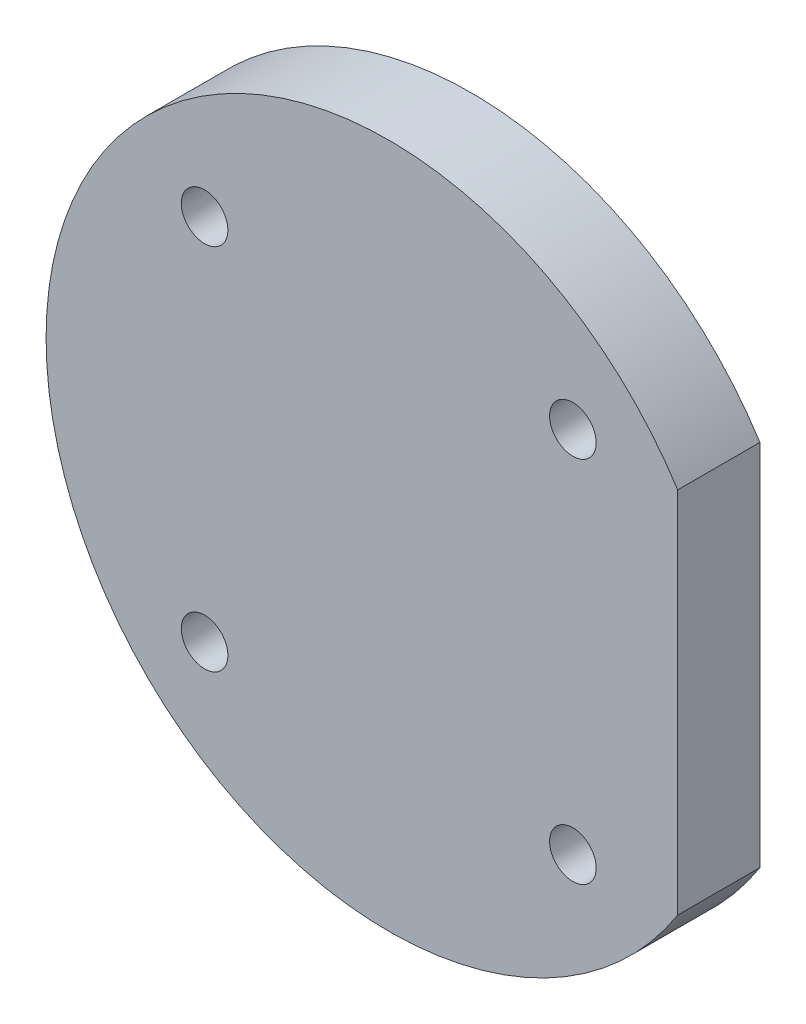
SolidWorks part; units mm, degrees
ref_plane "Plan de face" through (0, 0, 0) normal (0, 0, 1) x (1, 0, 0)
ref_plane "Plan de dessus" through (0, 0, 0) normal (0, 1, 0) x (1, 0, 0)
ref_plane "Plan de droite" through (0, 0, 0) normal (1, 0, 0) x (0, 0, -1)
sketch "Esquisse1" plane through (0, 0, 0) normal (0, 0, 1) x (1, 0, 0)
  circle A0 centre (0, 0) radius 25
  circle A1 centre (-13.435, 13.435) radius 1.7
  circle A2 centre (13.435, 13.435) radius 1.7
  circle A3 centre (13.435, -13.435) radius 1.7
  circle A4 centre (-13.435, -13.435) radius 1.7
  point P19 (0, 0)
  dimension "D1" = 50
  dimension "D5" = 19
  dimension "D6" = 3.4
  dimension "D4" = 4
extrude "Boss.-Extru.1" add sketch "Esquisse1" along normal blind 6
ref_plane "Plan1" through (0, 0, 0) normal (1, 0, 0) x (0, 0, -1)
sketch "Esquisse6" plane through (0, 0, 0) normal (0, 0, -1) x (-1, 0, 0)
  circle A0 centre (0, 0) radius 11
  dimension "D1" = 22
extrude "Enlèv. mat.-Extru.2" cut sketch "Esquisse6" against normal blind 3
fillet "Congé2" radius 0.5 1 edges at (-11, 0, 3)
sketch "Esquisse8" plane through (0, 0, 6) normal (0, 0, 1) x (1, 0, 0)
  line L0 (-6.5, 2) -> (6.5, 2) construction
  line L1 (6.5, 2) -> (6.5, -2) construction
  line L2 (6.5, -2) -> (-6.5, -2) construction
  line L3 (-6.5, 2) -> (-6.5, -2) construction
  line L4 (-6.25, 1.75) -> (-6.25, 2) construction
  line L5 (-6.25, 1.75) -> (-6.5, 1.75) construction
  line L6 (-6.25, -1.75) -> (-6.5, -1.75) construction
  line L7 (-6.25, -1.75) -> (-6.25, -2) construction
  line L8 (6.25, 1.75) -> (6.25, 2) construction
  line L9 (6.25, 1.75) -> (6.5, 1.75) construction
  line L10 (6.25, -1.75) -> (6.5, -1.75) construction
  line L11 (6.25, -1.75) -> (6.25, -2) construction
  line L12 (6.5, 0) -> (-6.5, 0) construction
  circle A0 centre (-6.25, 1.75) radius 0.25
  circle A1 centre (-6.25, -1.75) radius 0.25
  circle A2 centre (6.25, 1.75) radius 0.25
  circle A3 centre (6.25, -1.75) radius 0.25
sketch "Esquisse10" plane through (0, 0, 6) normal (0, 0, 1) x (1, 0, 0)
  line L0 (-10, 0) -> (10, 0) construction
  line L1 (10, 0) -> (10, 5) construction
  line L2 (10, 5) -> (-10, 5) construction
  line L3 (-10, 5) -> (-10, 0) construction
  line L4 (6.5, -2) -> (-6.5, -2) construction
  line L5 (-6.5, 2) -> (6.5, 2) construction
  line L6 (6.5, 2) -> (6.5, -2) construction
  line L7 (6.5, 0) -> (-6.5, 0) construction
  line L8 (9.2495, -0.5365) -> (9.2495, 3.4635) construction
  line L9 (10, 0) -> (10, -5) construction
  line L10 (10, -5) -> (-10, -5) construction
  line L11 (-10, -5) -> (-10, 0) construction
  line L12 (-6.25, -1.75) -> (-10, -5) construction
  line L13 (-5.7588, -2.3168) -> (-9.5088, -5.5668)
  line L14 (-6.7412, -1.1832) -> (-10.4912, -4.4332)
  line L15 (-6.25, 1.75) -> (-10, 5) construction
  line L16 (-6.7412, 1.1832) -> (-10.4912, 4.4332)
  line L17 (-5.7588, 2.3168) -> (-9.5088, 5.5668)
  line L18 (10, -5) -> (6.25, -1.75) construction
  line L19 (9.5088, -5.5668) -> (5.7588, -2.3168)
  line L20 (10.4912, -4.4332) -> (6.7412, -1.1832)
  line L21 (10, 5) -> (6.25, 1.75) construction
  line L22 (10.4912, 4.4332) -> (6.7412, 1.1832)
  line L23 (9.5088, 5.5668) -> (5.7588, 2.3168)
  arc A0 (-5.7588, -2.3168) -> (-6.7412, -1.1832) centre (-6.25, -1.75) ccw
  arc A1 (-10.4912, -4.4332) -> (-9.5088, -5.5668) centre (-10, -5) ccw
  arc A2 (-6.7412, 1.1832) -> (-5.7588, 2.3168) centre (-6.25, 1.75) ccw
  arc A3 (-9.5088, 5.5668) -> (-10.4912, 4.4332) centre (-10, 5) ccw
  arc A4 (9.5088, -5.5668) -> (10.4912, -4.4332) centre (10, -5) ccw
  arc A5 (6.7412, -1.1832) -> (5.7588, -2.3168) centre (6.25, -1.75) ccw
  arc A6 (10.4912, 4.4332) -> (9.5088, 5.5668) centre (10, 5) ccw
  arc A7 (5.7588, 2.3168) -> (6.7412, 1.1832) centre (6.25, 1.75) ccw
  point P12 (0, 0)
  point P18 (-8.125, -3.375)
  point P24 (-8.125, 3.375)
  point P31 (8.125, -3.375)
  point P38 (8.125, 3.375)
extrude "Boss.-Extru.6" add sketch "Esquisse10" against normal blind 6
sketch "Esquisse11" plane through (0, 0, 0) normal (0, 0, -1) x (-1, 0, 0)
  line L1 (10.2675, -2.5) -> (26.7116, -2.5)
  line L2 (10.2675, -2.5) -> (10.2675, 2.5)
  line L3 (10.2675, 2.5) -> (26.7116, 2.5)
  line L4 (26.7116, -2.5) -> (26.7116, 2.5)
  line L6 (26.7116, 0) -> (10.2675, 0) construction
  line L7 (-6.5, 0) -> (6.5, 0) construction
ref_plane "Plan2" through (-25, 0, 0) normal (-1, 0, 0) x (0, 0, 1)
sketch "Esquisse12" plane through (-25, 0, 0) normal (-1, 0, 0) x (0, 0, 1)
  ellipse E0 centre (0, 0) end of major axis (-3.5794, 0) minor radius 3
extrude "Enlèv. mat.-Extru.3" cut sketch "Esquisse12" against normal blind 15
sketch "Esquisse13" plane through (0, 0, 0) normal (0, 0, -1) x (-1, 0, 0)
  line L1 (24.9656, 5.5545) -> (6.3049, 5.5545)
  line L2 (24.9656, 5.5545) -> (24.9656, 7.0545)
  line L3 (24.9656, 7.0545) -> (6.3049, 7.0545)
  line L4 (6.3049, 5.5545) -> (6.3049, 7.0545)
revolve "Enlèvement de matière-Révolution1" cut sketch "Esquisse13" angle 360 about L3
sketch "Esquisse14" plane through (0, 0, 0) normal (0, 0, -1) x (-1, 0, 0)
  line L1 (24.3751, -5.5545) -> (5.9664, -5.5545)
  line L2 (24.3751, -5.5545) -> (24.3751, -7.0545)
  line L3 (24.3751, -7.0545) -> (5.9664, -7.0545)
  line L4 (5.9664, -5.5545) -> (5.9664, -7.0545)
  arc A0 (23.4909, 8.5545) -> (24.8193, -3) centre (0, 0) ccw construction
revolve "Enlèvement de matière-Révolution2" cut sketch "Esquisse14" angle 360 about L3
sketch "Esquisse15" plane through (0, 0, 0) normal (0, 0, -1) x (-1, 0, 0)
  line L1 (-21.0832, 13.435) -> (-29.047, 13.435)
  line L2 (-21.0832, 13.435) -> (-21.0832, -14.015)
  line L3 (-21.0832, -14.015) -> (-29.047, -14.015)
  line L4 (-29.047, 13.435) -> (-29.047, -14.015)
  arc A0 (23.4909, 8.5545) -> (23.4909, -8.5545) centre (0, 0) ccw construction
extrude "Enlèv. mat.-Extru.4" cut sketch "Esquisse15" against normal through all
equation "\"9.5.00mm\"=6"
